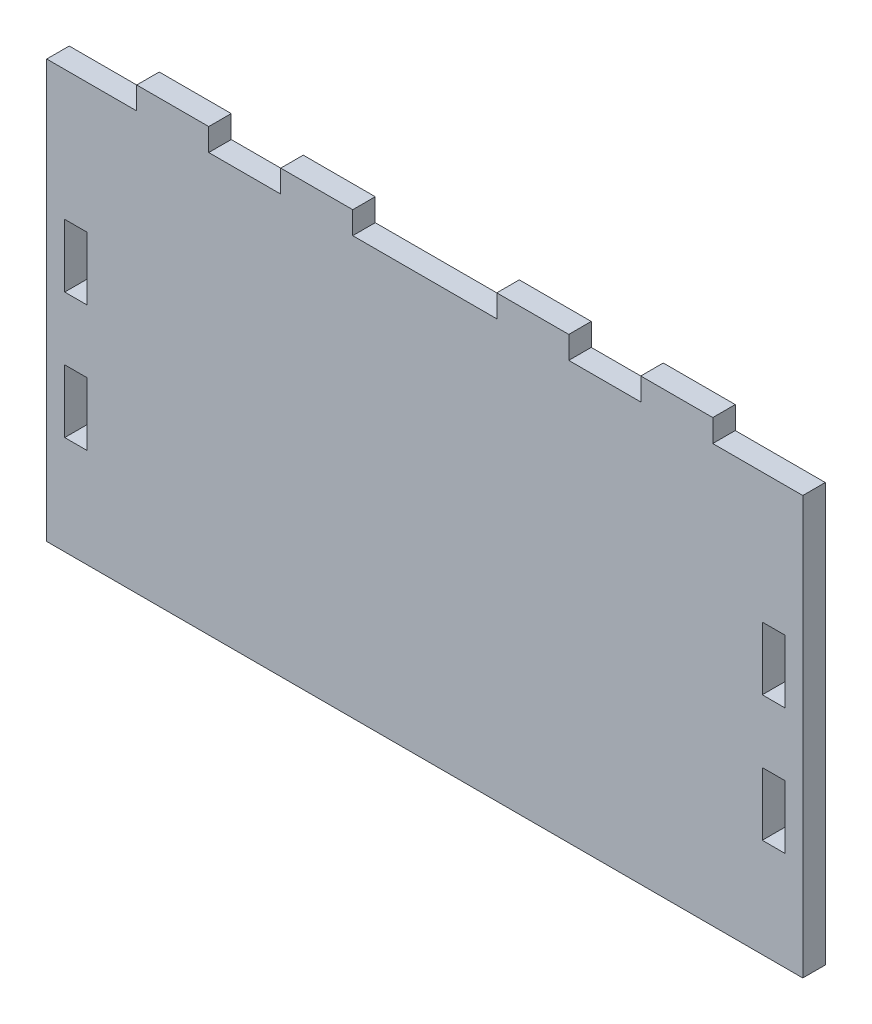
SolidWorks part; units mm, degrees
material "Beech"
ref_plane "Front" through (0, 0, 0) normal (0, 0, 1) x (1, 0, 0)
ref_plane "Top" through (0, 0, 0) normal (0, 1, 0) x (1, 0, 0)
ref_plane "Right" through (0, 0, 0) normal (1, 0, 0) x (0, 0, -1)
sketch "Sketch1" plane through (0, 0, 0) normal (0, 0, 1) x (1, 0, 0)
  line L0 (-42, -24.4632) -> (0, -24.4632) construction
  line L1 (-42, -24.4632) -> (-42, 24.4632) construction
  line L2 (0, -24.4632) -> (0, 24.4632) construction
  line L3 (-42, 24.4632) -> (0, 24.4632) construction
  line L4 (-42, -24.4632) -> (0, 24.4632) construction
  line L5 (0, -24.4632) -> (-42, 24.4632) construction
  line L6 (-42, 21.9632) -> (0, 21.9632) construction
  line L7 (-3.222, 0) -> (6.3832, 0) construction
  line L10 (-16, 21.9632) -> (-16, 24.4632)
  line L18 (-32, 21.9632) -> (-32, 24.4632)
  line L19 (-32, 24.4632) -> (-24, 24.4632)
  line L20 (-24, 21.9632) -> (-24, 24.4632)
  line L21 (-32, 21.9632) -> (-24, 24.4632) construction
  line L22 (-32, 24.4632) -> (-24, 21.9632) construction
  line L24 (-8, 21.9632) -> (-8, 24.4632)
  line L25 (-16, 24.4632) -> (-8, 24.4632)
  line L31 (-32, 21.9632) -> (-42, 21.9632)
  line L32 (-42, 21.9632) -> (-42, -24.4632)
  line L33 (-42, -24.4632) -> (42, -24.4632)
  line L35 (8, 21.9632) -> (-8, 21.9632)
  line L36 (-16, 21.9632) -> (-24, 21.9632)
  line L44 (42, 21.9632) -> (42, -24.4632)
  line L45 (32, 21.9632) -> (42, 21.9632)
  line L46 (32, 21.9632) -> (32, 24.4632)
  line L47 (32, 24.4632) -> (24, 24.4632)
  line L48 (24, 21.9632) -> (24, 24.4632)
  line L49 (16, 21.9632) -> (24, 21.9632)
  line L50 (16, 21.9632) -> (16, 24.4632)
  line L51 (16, 24.4632) -> (8, 24.4632)
  line L52 (8, 21.9632) -> (8, 24.4632)
  line L53 (-37.5, 0.5368) -> (-37.5, 7.5368)
  line L54 (-37.5, -13.4632) -> (-40, -13.4632)
  line L55 (-37.5, -13.4632) -> (-37.5, -6.4632)
  line L56 (-37.5, -6.4632) -> (-40, -6.4632)
  line L57 (-40, -13.4632) -> (-40, -6.4632)
  line L58 (-37.5, -13.4632) -> (-40, -6.4632) construction
  line L59 (-37.5, -6.4632) -> (-40, -13.4632) construction
  line L60 (-37.5, 0.5368) -> (-40, 0.5368)
  line L61 (-40, 0.5368) -> (-40, 7.5368)
  line L62 (-37.5, 7.5368) -> (-40, 7.5368)
  line L63 (37.5, -6.4632) -> (40, -6.4632)
  line L64 (40, -13.4632) -> (40, -6.4632)
  line L65 (37.5, -13.4632) -> (40, -13.4632)
  line L66 (37.5, -13.4632) -> (37.5, -6.4632)
  line L67 (37.5, 0.5368) -> (40, 0.5368)
  line L68 (40, 0.5368) -> (40, 7.5368)
  line L69 (37.5, 7.5368) -> (40, 7.5368)
  line L70 (37.5, 0.5368) -> (37.5, 7.5368)
  point P1 (-21, 0)
  point P12 (0, 0)
  point P24 (-28, 23.2132)
  point P55 (-38.75, -9.9632)
  point P68 (-32, -14.6632)
  point P69 (-32, -17.1632)
  point P70 (16, 23.2132)
  dimension "D1" = 2.5
  dimension "D2" = 42
  dimension "D3" = 48.9264
  dimension "D4" = 14.4264
  dimension "D6" = 10
  dimension "D7" = 8
  dimension "D10" = 8
  dimension "D11" = 7
  dimension "D12" = 2
  dimension "D13" = 2.5
  dimension "D16" = 7
  dimension "D8" = 2
  dimension "D15" = 2
extrude "Boss-Extrude1" add sketch "Sketch1" along normal blind 2.5
